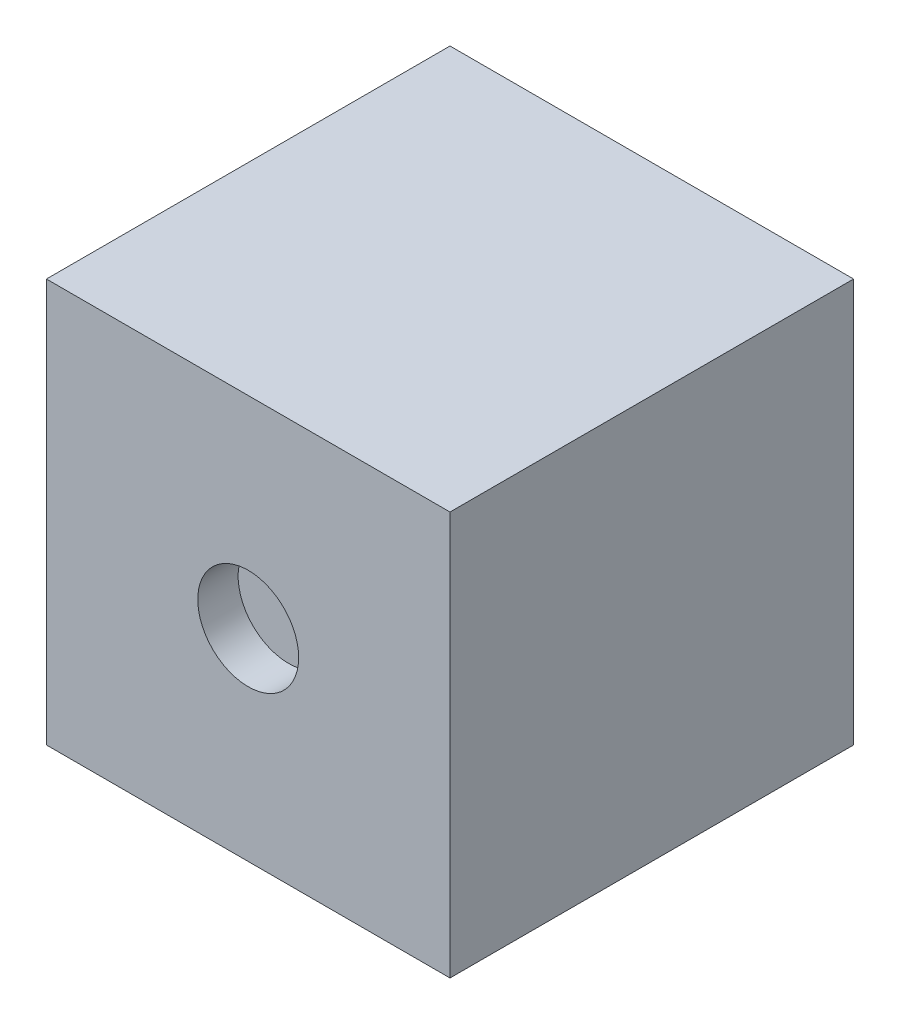
SolidWorks part; units mm, degrees
ref_plane "Plan de face" through (0, 0, 0) normal (0, 0, 1) x (1, 0, 0)
ref_plane "Plan de dessus" through (0, 0, 0) normal (0, 1, 0) x (1, 0, 0)
ref_plane "Plan de droite" through (0, 0, 0) normal (1, 0, 0) x (0, 0, -1)
sketch "Esquisse1" plane through (0, 0, 0) normal (0, 0, 1) x (1, 0, 0)
  line L1 (0, 0) -> (20, 0)
  line L2 (0, 0) -> (0, 20)
  line L3 (0, 20) -> (20, 20)
  line L4 (20, 0) -> (20, 20)
  dimension "D1" = 20
  dimension "D2" = 20
extrude "Boss.-Extru.1" add sketch "Esquisse1" against normal blind 20
sketch "Esquisse2" plane through (0, 0, 0) normal (0, 0, 1) x (1, 0, 0)
  line L0 (0, 0) -> (20, 20) construction
  line L1 (20, 20) -> (20, 0) construction
  line L2 (20, 0) -> (0, 20) construction
  circle A0 centre (10, 10) radius 2.5
  dimension "D1" = 5
extrude "Enlèv. mat.-Extru.1" cut sketch "Esquisse2" against normal blind 2
